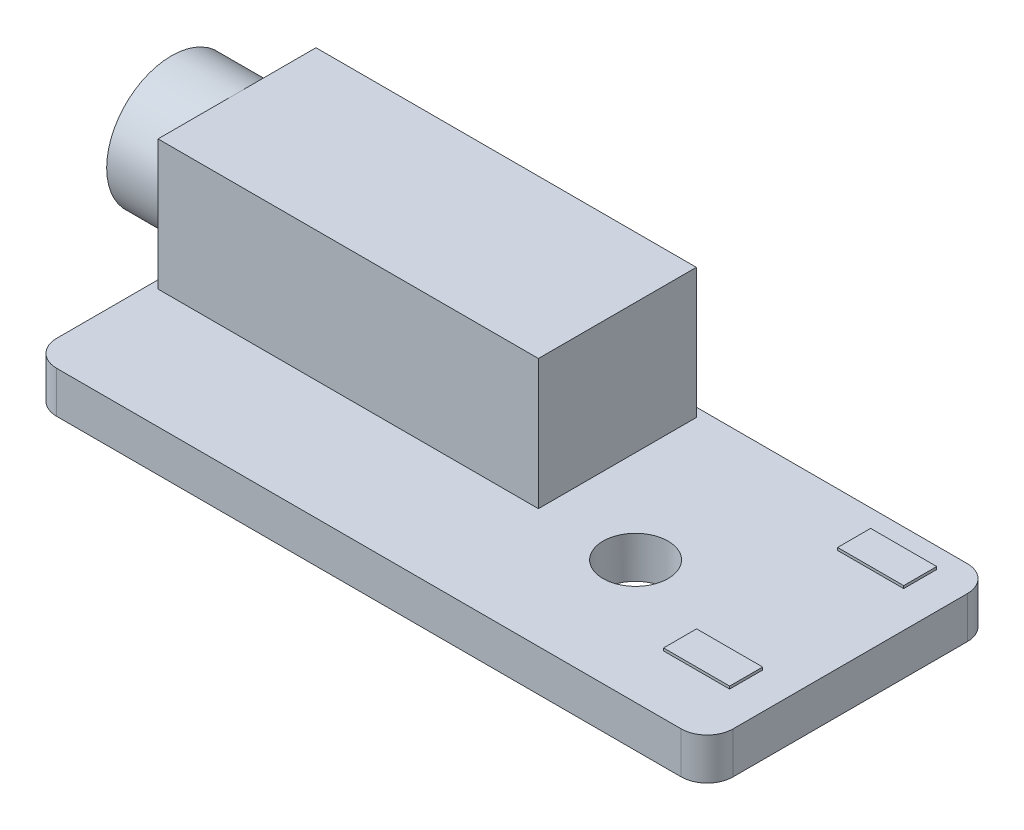
SolidWorks part; units mm, degrees
ref_plane "Front Plane" through (0, 0, 0) normal (0, 0, 1) x (1, 0, 0)
ref_plane "Top Plane" through (0, 0, 0) normal (0, 1, 0) x (1, 0, 0)
ref_plane "Right Plane" through (0, 0, 0) normal (1, 0, 0) x (0, 0, -1)
sketch "Sketch1" plane through (0, 0, 0) normal (0, 1, 0) x (1, 0, 0)
  line L1 (12, 5.5) -> (-12, 5.5)
  line L2 (13, 4.5) -> (13, -4.5)
  line L3 (12, -5.5) -> (-12, -5.5)
  line L4 (-13, 4.5) -> (-13, -4.5)
  line L5 (13, 5.5) -> (-13, -5.5) construction
  line L6 (13, -5.5) -> (-13, 5.5) construction
  arc A0 (12, 5.5) -> (13, 4.5) centre (12, 4.5) cw
  arc A1 (13, -4.5) -> (12, -5.5) centre (12, -4.5) cw
  arc A2 (-12, -5.5) -> (-13, -4.5) centre (-12, -4.5) cw
  arc A3 (-12, 5.5) -> (-13, 4.5) centre (-12, 4.5) ccw
  point P0 (0, 0)
  dimension "D3" = 1
  dimension "D1" = 26
  dimension "D2" = 11
extrude "Boss-Extrude1" add sketch "Sketch1" along normal blind 1.6
sketch "Sketch2" plane through (0, 1.6, 0) normal (0, 1, 0) x (1, 0, 0)
  line L0 (-13, -4.5) -> (-13, -5.5) construction
  line L1 (9.07, 4.715) -> (11.61, 4.715)
  line L2 (9.07, 4.715) -> (9.07, 3.445)
  line L3 (9.07, 3.445) -> (11.61, 3.445)
  line L4 (11.61, 4.715) -> (11.61, 3.445)
  line L5 (9.07, 4.715) -> (11.61, 3.445) construction
  line L6 (9.07, 3.445) -> (11.61, 4.715) construction
  line L7 (9.07, -1.975) -> (11.61, -1.975)
  line L8 (9.07, -1.975) -> (9.07, -3.245)
  line L9 (9.07, -3.245) -> (11.61, -3.245)
  line L10 (11.61, -1.975) -> (11.61, -3.245)
  line L11 (9.07, -1.975) -> (11.61, -3.245) construction
  line L12 (9.07, -3.245) -> (11.61, -1.975) construction
  line L13 (-13, -5.5) -> (-12, -5.5) construction
  line L14 (-12, -5.5) -> (12, -5.5) construction
  point P0 (10.34, 4.08)
  point P5 (10.34, -2.61)
  dimension "D1" = 2.54
  dimension "D2" = 1.27
  dimension "D3" = 23.34
  dimension "D4" = 2.89
  dimension "D5" = 9.58
extrude "Boss-Extrude2" add sketch "Sketch2" along normal blind 0.1
sketch "Sketch3" plane through (0, 1.6, 0) normal (0, 1, 0) x (1, 0, 0)
  line L0 (-13, 4.5) -> (-13, -4.5) construction
  line L1 (-12.69, 5.155) -> (1.93, 5.155)
  line L2 (-12.69, 5.155) -> (-12.69, -0.915)
  line L3 (-12.69, -0.915) -> (1.93, -0.915)
  line L4 (1.93, 5.155) -> (1.93, -0.915)
  line L5 (-12.69, 5.155) -> (1.93, -0.915) construction
  line L6 (-12.69, -0.915) -> (1.93, 5.155) construction
  line L7 (-12, -5.5) -> (12, -5.5) construction
  point P0 (-5.38, 2.12)
  dimension "D1" = 14.62
  dimension "D2" = 6.07
  dimension "D3" = 7.62
  dimension "D4" = 7.62
extrude "Boss-Extrude3" add sketch "Sketch3" along normal blind 5
sketch "Sketch4" plane through (-12.69, 0, 0) normal (-1, 0, 0) x (0, 0, 1)
  line L0 (-5.155, 4.1) -> (0.915, 4.1) construction
  line L1 (-5.155, 6.6) -> (-5.155, 1.6) construction
  line L2 (0.915, 6.6) -> (0.915, 1.6) construction
  circle A0 centre (-2.12, 4.1) radius 2.49
  circle A1 centre (-2.12, 4.1) radius 1.795
  dimension "D1" = 3.59
  dimension "D2" = 4.98
extrude "Boss-Extrude5" add sketch "Sketch4" along normal blind 2.52
sketch "Sketch5" plane through (0, 1.6, 0) normal (0, 1, 0) x (1, 0, 0)
  line L0 (-13, 4.5) -> (-13, -4.5) construction
  line L1 (-12, -5.5) -> (12, -5.5) construction
  circle A0 centre (5.5, -0.75) radius 1.25
  dimension "D1" = 2.5
  dimension "D2" = 18.5
  dimension "D3" = 4.75
extrude "Cut-Extrude1" cut sketch "Sketch5" against normal through all both and the other way through all
